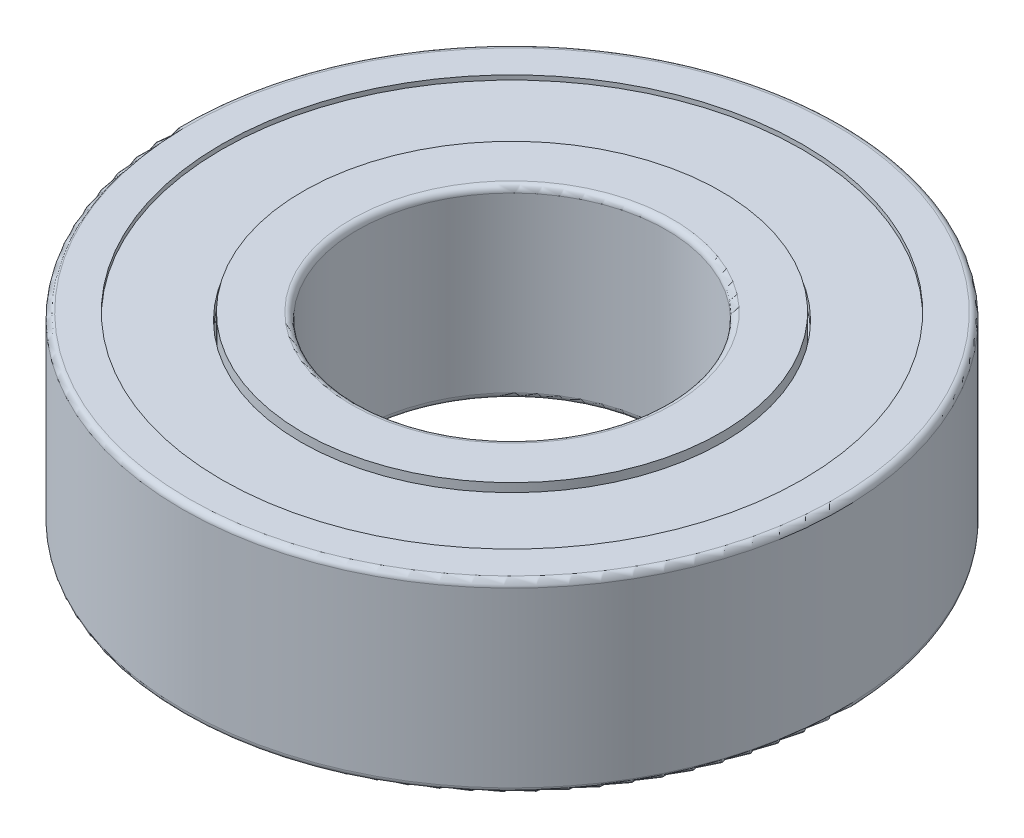
SolidWorks part; units mm, degrees
ref_plane "Front Plane" through (0, 0, 0) normal (0, 0, 1) x (1, 0, 0)
ref_plane "Top Plane" through (0, 0, 0) normal (0, 1, 0) x (1, 0, 0)
ref_plane "Right Plane" through (0, 0, 0) normal (1, 0, 0) x (0, 0, -1)
sketch "Sketch1" plane through (0, 0, 0) normal (0, 0, 1) x (1, 0, 0)
  line L0 (-7.5, 4.5) -> (-10.15, 1.6941) construction
  line L1 (-7.5, 4.5) -> (-10.15, 4.5)
  line L2 (-7.5, 4.5) -> (-7.5, -4.5)
  line L3 (-7.5, -4.5) -> (-10.15, -4.5)
  line L4 (-10.15, 4.5) -> (-10.15, 1.7687)
  line L5 (-7.5, 4.5) -> (-10.15, -4.5) construction
  line L6 (-7.5, -4.5) -> (-10.15, 4.5) construction
  line L7 (-14.1, 4.5) -> (-16, 4.5)
  line L8 (-14.1, -4.28) -> (-14.1, -4.5)
  line L9 (-14.1, -4.5) -> (-16, -4.5)
  line L10 (-16, 4.5) -> (-16, -4.5)
  line L11 (-13.35, -3.71) -> (-14.1, -3.71) construction
  line L12 (-7.5, 4.5) -> (-16, -4.5) construction
  line L13 (-13.35, -1.6941) -> (-13.3876, -1.7339) construction
  line L14 (-13.35, -1.7687) -> (-13.35, -3.58)
  line L15 (-10.15, -1.7687) -> (-10.15, -4.5)
  line L17 (-13.35, 3.71) -> (-14.38, 3.71) construction
  line L18 (-14.1, 4.28) -> (-14.38, 4.28) construction
  line L21 (-14.38, 4.28) -> (-14.1, 4.28)
  line L22 (-14.38, 3.71) -> (-13.35, 3.71)
  line L24 (-13.35, 3.58) -> (-14.38, 3.71)
  line L25 (-14.1, 4.5) -> (-14.1, 4.28) construction
  line L26 (-14.1, 4.28) -> (-14.1, 4.5)
  line L27 (-13.35, 3.58) -> (-13.35, 1.7687)
  line L31 (-13.35, -3.71) -> (-14.1, -3.71)
  line L32 (-13.35, -3.58) -> (-14.1, -3.71)
  arc A0 (-10.15, -1.7687) -> (-10.15, 1.7687) centre (-11.75, 0) ccw
  arc A1 (-13.35, 1.7687) -> (-13.35, -1.7687) centre (-11.75, 0) ccw
  arc A2 (-14.38, 4.28) -> (-14.38, 3.71) centre (-14.38, 3.995) ccw
  arc A3 (-14.1, -4.28) -> (-14.1, -3.71) centre (-14.1, -3.995) cw
  point P0 (-8.825, 0)
  point P5 (-14.675, 0)
  dimension "D5" = 0.79
  dimension "D1" = 9
  dimension "D2" = 0.79
  dimension "D3" = 7.5
  dimension "D4" = 16
  dimension "D6" = 0.22
  dimension "D8" = 0.57
  dimension "D10" = 1.9
sketch "Sketch2" plane through (0, 0, 0) normal (0, 0, 1) x (1, 0, 0)
  line L0 (-11.75, 2.38) -> (-11.75, -2.38)
  arc A0 (-11.75, -2.38) -> (-11.75, 2.38) centre (-11.75, 0) ccw
  dimension "D1" = 2.38
revolve "Revolve1" add sketch "Sketch2" angle 360 about L0
ref_axis "Axis1" through (0, 4.95, 0) along (0, -1, 0)
revolve "Revolve2" add sketch "Sketch1" angle 360 about axis through (0, 4.95, 0) along (0, -1, 0)
pattern_circular "CirPattern1" count 9 over 360 about axis through (0, 0, 0) along (0, 1, 0) of bodies 101
fillet "Fillet1" radius 0.3 2 edges at (0, -4.5, 16) (0, 4.5, 16)
fillet "Fillet2" radius 0.3 2 edges at (0, 4.5, 7.5) (0, -4.5, 7.5)
ref_plane "Plane1" through (0, 3.58, 0) normal (0, -1, 0) x (-1, 0, 0)
sketch "Sketch3" plane through (0, 3.58, 0) normal (0, -1, 0) x (-1, 0, 0)
  circle A0 centre (0, 0) radius 14.385
  circle A1 centre (0, 0) radius 10.25
extrude "Boss-Extrude4" add sketch "Sketch3" against normal blind 0.57
ref_plane "Plane2" through (0, -3.58, 0) normal (0, -1, 0) x (-1, 0, 0)
sketch "Sketch6" plane through (0, -3.58, 0) normal (0, -1, 0) x (-1, 0, 0)
  circle A0 centre (0, 0) radius 10.25
  circle A1 centre (0, 0) radius 14.385
extrude "Boss-Extrude6" add sketch "Sketch6" along normal blind 0.57
